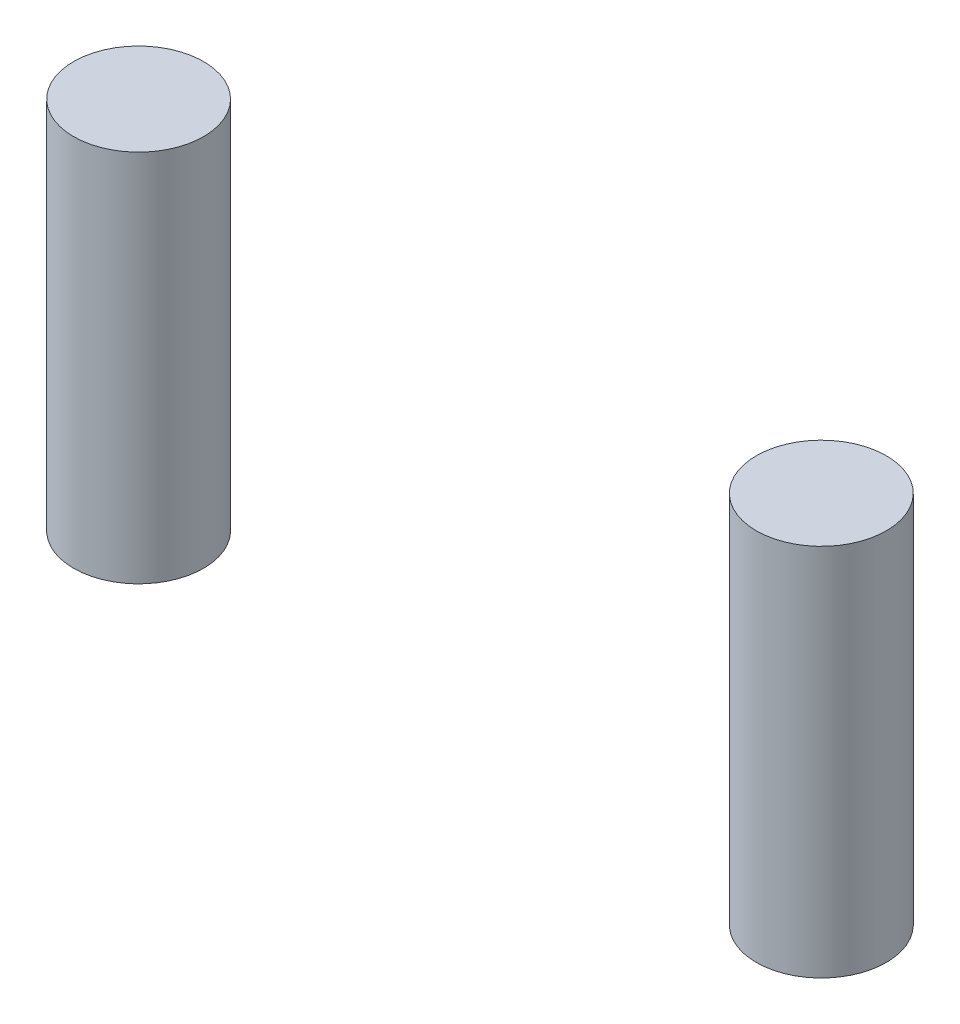
SolidWorks part; units mm, degrees
ref_plane "Front Plane" through (0, 0, 0) normal (0, 0, 1) x (1, 0, 0)
ref_plane "Top Plane" through (0, 0, 0) normal (0, 1, 0) x (1, 0, 0)
ref_plane "Right Plane" through (0, 0, 0) normal (1, 0, 0) x (0, 0, -1)
ref_plane "Plane1" through (0, -108, 0) normal (0, 1, 0) x (1, 0, 0)
sketch "Sketch1" plane through (0, -108, 0) normal (0, 1, 0) x (1, 0, 0)
  circle A0 centre (-10.5, -26) radius 2
extrude "Boss-Extrude1" add sketch "Sketch1" along normal blind 11.5
sketch "Sketch2" plane through (0, -108, 0) normal (0, 1, 0) x (1, 0, 0)
  circle A0 centre (10.5, -26) radius 2
extrude "Boss-Extrude2" add sketch "Sketch2" along normal blind 11.5
